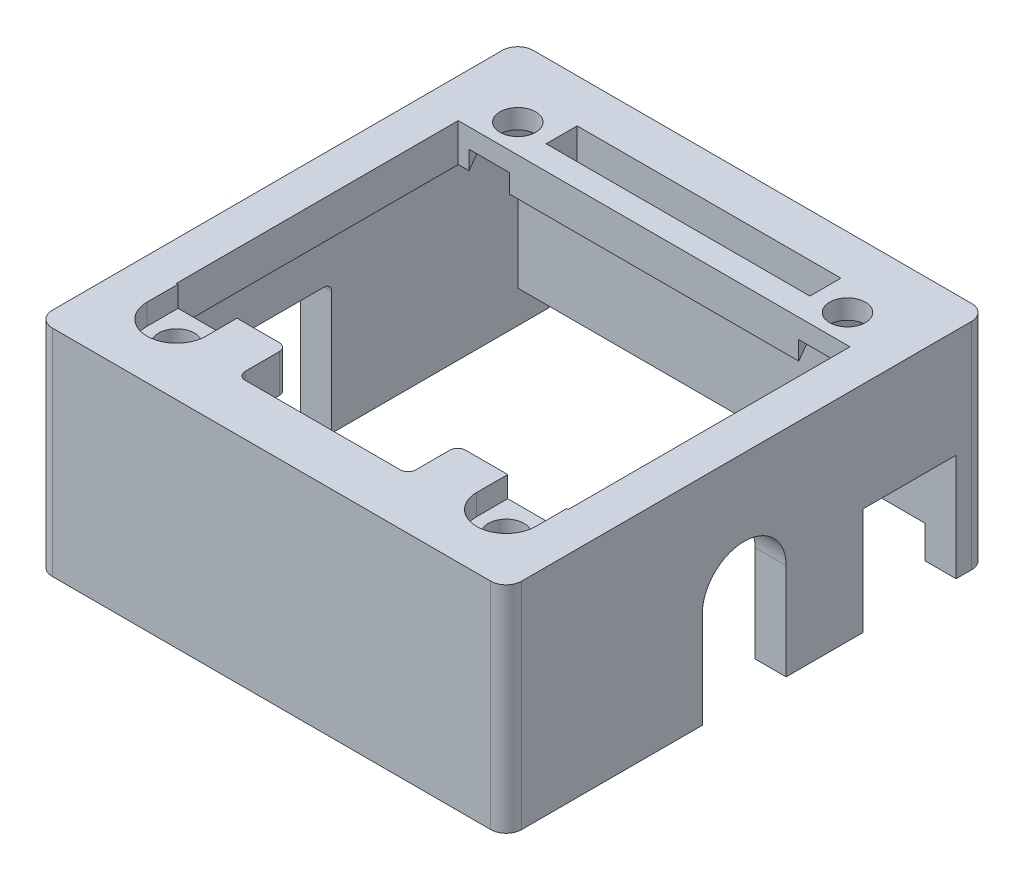
SolidWorks part; units mm, degrees
material "玻璃"
ref_plane "前视基准面" through (0, 0, 0) normal (0, 0, 1) x (1, 0, 0)
ref_plane "上视基准面" through (0, 0, 0) normal (0, 1, 0) x (1, 0, 0)
ref_plane "右视基准面" through (0, 0, 0) normal (1, 0, 0) x (0, 0, -1)
sketch "草图1" plane through (0, 0, 0) normal (0, 1, 0) x (1, 0, 0)
  line L5 (13.125, -13.5) -> (-13.125, -13.5)
  line L6 (13.125, -13.5) -> (13.125, 13.5)
  line L11 (13.125, 13.5) -> (-13.125, 13.5)
  line L12 (-13.125, -13.5) -> (-13.125, 13.5)
  line L13 (13.125, -13.5) -> (-13.125, 13.5) construction
  line L14 (13.125, 13.5) -> (-13.125, -13.5) construction
  line L15 (15.125, -15.5) -> (-15.125, -15.5)
  line L16 (15.125, -15.5) -> (15.125, 15.5)
  line L17 (15.125, 15.5) -> (-15.125, 15.5)
  line L18 (-15.125, -15.5) -> (-15.125, 15.5)
  line L19 (15.125, -15.5) -> (-15.125, 15.5) construction
  line L20 (15.125, 15.5) -> (-15.125, -15.5) construction
  point P0 (0, 0)
  point P6 (0, 0)
  dimension "D1" = 26.25
  dimension "D2" = 27
  dimension "D3" = 2
  dimension "D4" = 2
extrude "凸台-拉伸1" add sketch "草图1" against normal blind 11.42
sketch "草图2" plane through (0, 0, 0) normal (0, 1, 0) x (1, 0, 0)
  line L5 (15.125, -15.5) -> (-15.125, -15.5)
  line L6 (15.125, -15.5) -> (15.125, 15.5)
  line L7 (15.125, 15.5) -> (-15.125, 15.5)
  line L8 (-15.125, -15.5) -> (-15.125, 15.5)
  line L9 (15.125, -15.5) -> (-15.125, 15.5) construction
  line L10 (15.125, 15.5) -> (-15.125, -15.5) construction
  point P0 (0, 0)
extrude "凸台-拉伸2" add sketch "草图2" along normal blind 2.45
sketch "草图3" plane through (0, 0, 0) normal (0, 1, 0) x (1, 0, 0)
  line L0 (-12.625, 9.16) -> (12.625, 9.16)
  line L1 (-12.625, 9.16) -> (-12.625, -9)
  line L2 (12.625, 9.16) -> (12.625, -9)
  line L4 (12.625, -13) -> (-12.625, -13) construction
  line L5 (12.625, -13) -> (12.625, 13) construction
  line L6 (12.625, 13) -> (-12.625, 13) construction
  line L7 (-12.625, -13) -> (-12.625, 13) construction
  line L8 (12.625, -13) -> (-12.625, 13) construction
  line L9 (12.625, 13) -> (-12.625, -13) construction
  line L10 (-12.625, -9) -> (12.625, -9)
  point P0 (0, 0)
  dimension "D1" = 3.84
  dimension "D2" = 4
extrude "切除-拉伸1" cut sketch "草图3" along normal blind 2.45
sketch "草图4" plane through (0, 0, 0) normal (0, 1, 0) x (1, 0, 0)
  line L0 (0, 0) -> (0, 11) construction
  line L1 (12.625, -13) -> (-12.625, -13) construction
  line L2 (12.625, -13) -> (12.625, 13) construction
  line L3 (12.625, 13) -> (-12.625, 13) construction
  line L4 (-12.625, -13) -> (-12.625, 13) construction
  line L5 (12.625, -13) -> (-12.625, 13) construction
  line L6 (12.625, 13) -> (-12.625, -13) construction
  line L7 (0, 0) -> (-10.625, 0) construction
  circle A0 centre (-10.625, 11) radius 1.15
  circle A4 centre (-10.625, -11) radius 1.15
  circle A5 centre (10.625, 11) radius 1.15
  circle A6 centre (10.625, -11) radius 1.15
  point P0 (0, 0)
  dimension "D1" = 2
  dimension "D2" = 2
extrude "切除-拉伸3" cut sketch "草图4" along normal blind 2.45
sketch "草图5" plane through (0, 0, 0) normal (0, 1, 0) x (1, 0, 0)
  line L0 (12.625, 13) -> (-12.625, 13) construction
  line L1 (-9.4414, 8.95) -> (-8.2579, 11)
  line L2 (-8.2579, 11) -> (-9.4414, 13.05)
  line L3 (-9.4414, 13.05) -> (-11.8086, 13.05)
  line L4 (-11.8086, 13.05) -> (-12.9921, 11)
  line L5 (-12.9921, 11) -> (-11.8086, 8.95)
  line L6 (-11.8086, 8.95) -> (-9.4414, 8.95)
  line L7 (0, 0) -> (0, 13) construction
  line L8 (11.8086, 8.95) -> (9.4414, 8.95)
  line L9 (12.9921, 11) -> (11.8086, 8.95)
  line L10 (11.8086, 13.05) -> (12.9921, 11)
  line L11 (9.4414, 13.05) -> (11.8086, 13.05)
  line L12 (8.2579, 11) -> (9.4414, 13.05)
  line L13 (9.4414, 8.95) -> (8.2579, 11)
  circle A0 centre (-10.625, 11) radius 2.05 construction
  circle A1 centre (10.625, 11) radius 2.05 construction
  dimension "D1" = 4.1
  dimension "D2" = 0
  dimension "D3" = 0
extrude "切除-拉伸4" cut sketch "草图5" along normal blind 1.2
sketch "草图6" plane through (0, 2.45, 0) normal (0, 1, 0) x (1, 0, 0)
  circle A0 centre (-10.625, -11) radius 1.9
  circle A1 centre (10.625, -11) radius 1.9
extrude "切除-拉伸5" cut sketch "草图6" against normal blind 1.35
sketch "草图7" plane through (0, 0, 0) normal (0, 1, 0) x (1, 0, 0)
  line L0 (0, 0) -> (0, -13) construction
  line L1 (12.625, -13) -> (-12.625, -13) construction
  line L2 (-12.625, -9) -> (12.625, -9) construction
  line L4 (-5.5, -9) -> (-5.5, -12.2)
  line L5 (5.5, -9) -> (5.5, -12.2)
  line L6 (-5.5, -12.2) -> (5.5, -12.2)
  line L7 (-5.5, -9) -> (5.5, -9)
  point P5 (0, -9)
  point P11 (0, -9)
extrude "切除-拉伸7" cut sketch "草图7" along normal blind 2.45
sketch "草图8" plane through (0, 0, 0) normal (0, 1, 0) x (1, 0, 0)
  line L0 (0, 0) -> (0, 13) construction
  line L1 (12.625, 13) -> (-12.625, 13) construction
  line L3 (-10.625, 11) -> (10.625, 11) construction
  line L7 (-10.625, 11) -> (-10.625, 10.7) construction
  line L8 (-10.625, 10.7) -> (-8.5, 10.7) construction
  line L9 (-8.5, 10.7) -> (8.5, 10.7)
  line L11 (-8.5, 12.7) -> (8.5, 12.7)
  line L12 (12.625, 13) -> (-12.625, 13) construction
  line L13 (-8.5, 12.7) -> (-8.5, 10.7)
  line L14 (8.5, 12.7) -> (8.5, 10.7)
  point P8 (0, 13)
  dimension "D1" = 0.3
  dimension "D2" = 0.3
extrude "切除-拉伸9" cut sketch "草图8" along normal blind 2.45
fillet "圆角1" radius 1 4 edges at (-15.125, -4.485, 15.5) (15.125, -4.485, 15.5) (15.125, -4.485, -15.5) (-15.125, -4.485, -15.5)
sketch "草图12" plane through (13.125, 0, 0) normal (-1, 0, 0) x (0, 0, 1)
  line L0 (-13.5, -11.42) -> (-13, -11.42) construction
  line L1 (13.5, -11.42) -> (-13.5, -11.42) construction
  line L2 (-13, -11.42) -> (-13, 0) construction
  line L3 (13.5, 0) -> (-13.5, 0) construction
  line L4 (-13.5, -11.42) -> (-13.5, 0) construction
  line L5 (-13.5, -11.42) -> (-7.5, -11.42)
  line L6 (-13.5, -11.42) -> (-13.5, -4.52)
  line L8 (-7.5, -11.42) -> (-7.5, -4.52)
  line L9 (-13.5, -4.52) -> (-7.5, -4.52)
  dimension "D1" = 0.5
extrude "切除-拉伸10" cut sketch "草图12" against normal blind 2
sketch "草图14" plane through (13.125, 0, 0) normal (-1, 0, 0) x (0, 0, 1)
  line L0 (-13, -11.42) -> (0.157, -11.42) construction
  line L1 (13.5, -11.42) -> (-7.5, -11.42) construction
  line L2 (0.157, -11.42) -> (0.157, 0) construction
  line L3 (-2.543, -5.2) -> (-2.543, -11.42)
  line L5 (2.857, -5.2) -> (2.857, -11.42)
  circle A1 centre (0.157, -5.2) radius 2.7
  line M4 (-7.5, -4.52) -> (-7.5, -11.42)
  line M5 (-7.5, -11.42) -> (13.5, -11.42)
  dimension "D1" = 5.2
  dimension "D2" = 0
extrude "切除-拉伸11" cut sketch "草图14" against normal blind 2 contours A1 L3 L5 M5 | A1 M4
sketch "草图15" plane through (-13.125, 0, 0) normal (1, 0, 0) x (0, 0, -1)
  line L0 (-13, 0) -> (-13, -11.42) construction
  line L1 (13.5, 0) -> (-13.5, 0) construction
  line L2 (13.5, -11.42) -> (-13.5, -11.42) construction
  line L3 (-13.5, -11.42) -> (-13.5, 0) construction
  line L4 (-13, -11.42) -> (-8, -11.42) construction
  line L5 (-8, -11.42) -> (1.5, -11.42)
  line L6 (-8, -11.42) -> (-8, -3.02)
  line L7 (1.5, -11.42) -> (1.5, -3.02)
  line L9 (1.5, -3.02) -> (-8, -3.02)
  dimension "D1" = 0.5
extrude "切除-拉伸12" cut sketch "草图15" against normal blind 2
fillet "圆角2" radius 0.5 2 edges at (-14.125, -3.02, 8) (-14.125, -3.02, -1.5)
fillet "圆角3" radius 0.5 4 edges at (5.5, 1.225, 12.2) (-5.5, 1.225, 12.2) (5.5, 1.225, 9) (-5.5, 1.225, 9)
sketch "草图17" plane through (0, 0, -13.5) normal (0, 0, 1) x (1, 0, 0)
  line L0 (-13.125, -11.42) -> (-13.125, -9.32)
  line L1 (-13.125, -11.42) -> (-13.125, 0) construction
  line L2 (13.125, -4.2048) -> (13.125, -11.42) construction
  line L3 (13.125, -4.52) -> (13.125, 0) construction
  line L4 (15.125, -11.42) -> (-13.125, -11.42) construction
  line L5 (-13.125, -9.32) -> (13.125, -9.32)
  line L6 (13.125, -9.32) -> (13.125, -11.42)
  line L7 (13.125, -11.42) -> (-13.125, -11.42)
extrude "切除-拉伸19" cut sketch "草图17" against normal up to next
sketch "草图18" plane through (0, 2.45, 0) normal (0, 1, 0) x (1, 0, 0)
  line L0 (-8.725, -11) -> (-8.725, -9)
  line L1 (-12.625, -9) -> (-6, -9) construction
  line L2 (-12.525, -11) -> (-12.525, -9)
  line L3 (-12.525, -9) -> (-8.725, -9)
  line L4 (-12.525, -11) -> (-8.725, -11)
  line L5 (0, 0) -> (0, -9) construction
  line L6 (12.525, -11) -> (8.725, -11)
  line L7 (12.525, -9) -> (8.725, -9)
  line L8 (12.525, -11) -> (12.525, -9)
  line L9 (8.725, -11) -> (8.725, -9)
  circle A0 centre (-10.625, -11) radius 1.9 construction
  circle A1 centre (-10.625, -11) radius 1.9 construction
extrude "切除-拉伸20" cut sketch "草图18" against normal blind 1.35
